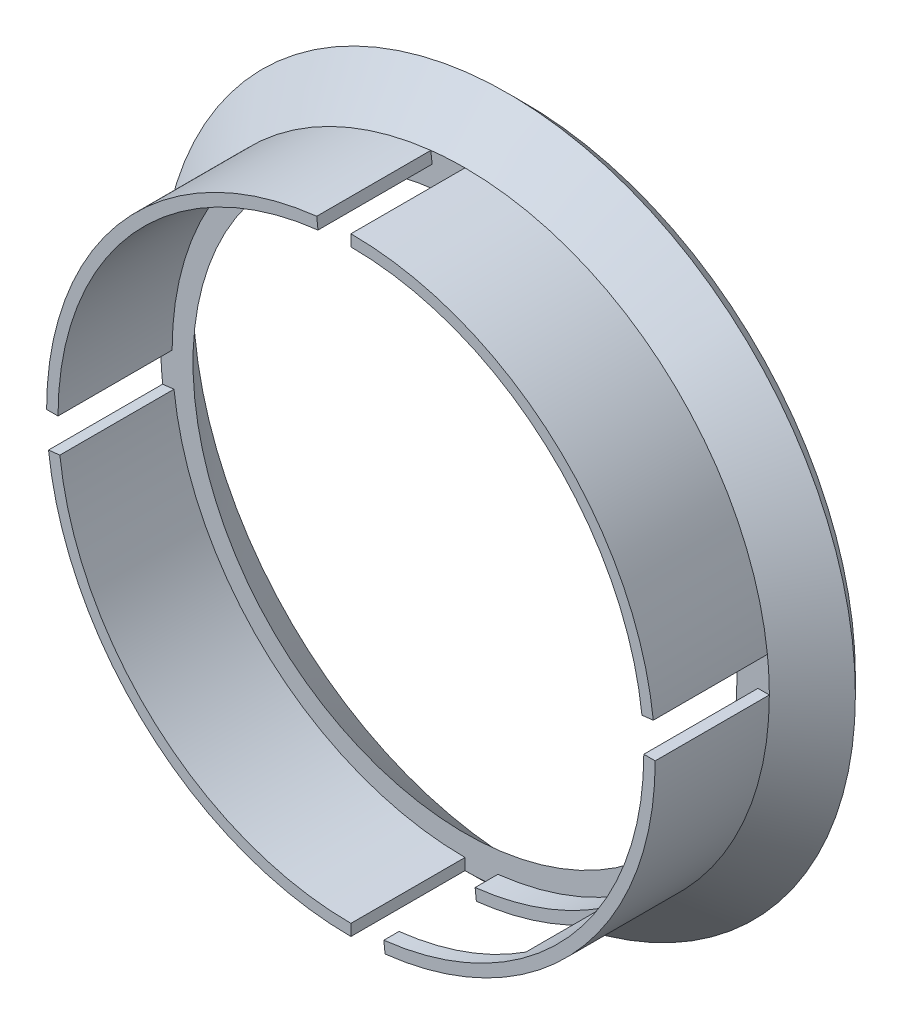
SolidWorks part; units mm, degrees
ref_plane "Alzado" through (0, 0, 0) normal (0, 0, 1) x (1, 0, 0)
ref_plane "Planta" through (0, 0, 0) normal (0, 1, 0) x (1, 0, 0)
ref_plane "Vista lateral" through (0, 0, 0) normal (1, 0, 0) x (0, 0, -1)
sketch "Croquis1" plane through (0, 0, 0) normal (0, 0, 1) x (1, 0, 0)
  line L0 (0, 40) -> (0, 38.5)
  line L1 (-4.4929, 39.7469) -> (-4.3244, 38.2564)
  line L2 (-38.5, 0) -> (-40, 0)
  line L3 (-39.7469, -4.4929) -> (-38.2564, -4.3244)
  line L4 (0, -40) -> (0, -38.5)
  line L5 (4.4929, -39.7469) -> (4.3244, -38.2564)
  line L6 (38.5, 0) -> (40, 0)
  line L7 (39.7469, 4.4929) -> (38.2564, 4.3244)
  circle A0 centre (0, 0) radius 40
  circle A1 centre (0, 0) radius 38.5
  dimension "D1" = 77
  dimension "0" = 80
  dimension "D2" = 4.5
  dimension "D3" = 4.5
  dimension "D4" = 4.5
  dimension "D5" = 4.5
extrude "Saliente-Extruir1" add sketch "Croquis1" along normal blind 15 contours A1 L1 A0 L2 | A1 L3 A0 L4 | A1 L7 A0 L0 | A1 L5 A0 L6
sketch "Croquis2" plane through (0, 0, 0) normal (0, 1, 0) x (1, 0, 0)
  line L0 (-40, 0) -> (-45.6569, 5.6569)
  line L1 (-45.6569, 5.6569) -> (-43.5355, 7.7782)
  line L2 (-43.5355, 7.7782) -> (-35.7574, 0)
  line L3 (-4.4929, 0) -> (-40, 0) construction
  line L4 (0, 0) -> (0, 20.2639) construction
  line L5 (-35.7574, 0) -> (-40, 0)
  dimension "D1" = 3
  dimension "D2" = 11
  dimension "D3" = 45
revolve "Revolución1" add sketch "Croquis2" angle 360 about L4
sketch "Croquis3" plane through (0, 0, 0) normal (0, 1, 0) x (1, 0, 0)
  line L1 (-4, -3) -> (21, -3)
  line L2 (-4, -3) -> (-4, -13)
  line L3 (-4, -13) -> (21, -13)
  line L4 (21, -3) -> (21, -13)
  line L8 (-39.7469, 0) -> (0, 0) construction
  line L9 (40, -15) -> (40, 0) construction
  dimension "D1" = 3
  dimension "D2" = 25
  dimension "D3" = 10
  dimension "D4" = 19
extrude "Cortar-Extruir1" cut sketch "Croquis3" against normal up to next
